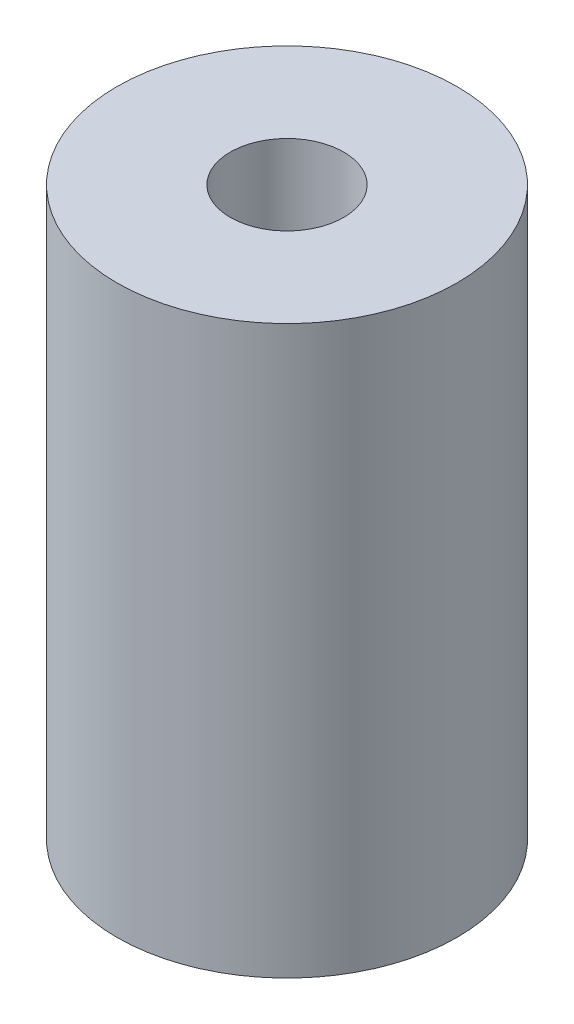
SolidWorks part; units mm, degrees
ref_plane "Front Plane" through (0, 0, 0) normal (0, 0, 1) x (1, 0, 0)
ref_plane "Top Plane" through (0, 0, 0) normal (0, 1, 0) x (1, 0, 0)
ref_plane "Right Plane" through (0, 0, 0) normal (1, 0, 0) x (0, 0, -1)
sketch "Sketch1" plane through (0, 0, 0) normal (0, 1, 0) x (1, 0, 0)
  circle A0 centre (0, 0) radius 1.5
  circle A1 centre (0, 0) radius 4.5
  dimension "D1" = 9
  dimension "D2" = 3
extrude "Boss-Extrude1" add sketch "Sketch1" along normal blind 15 contours A0
